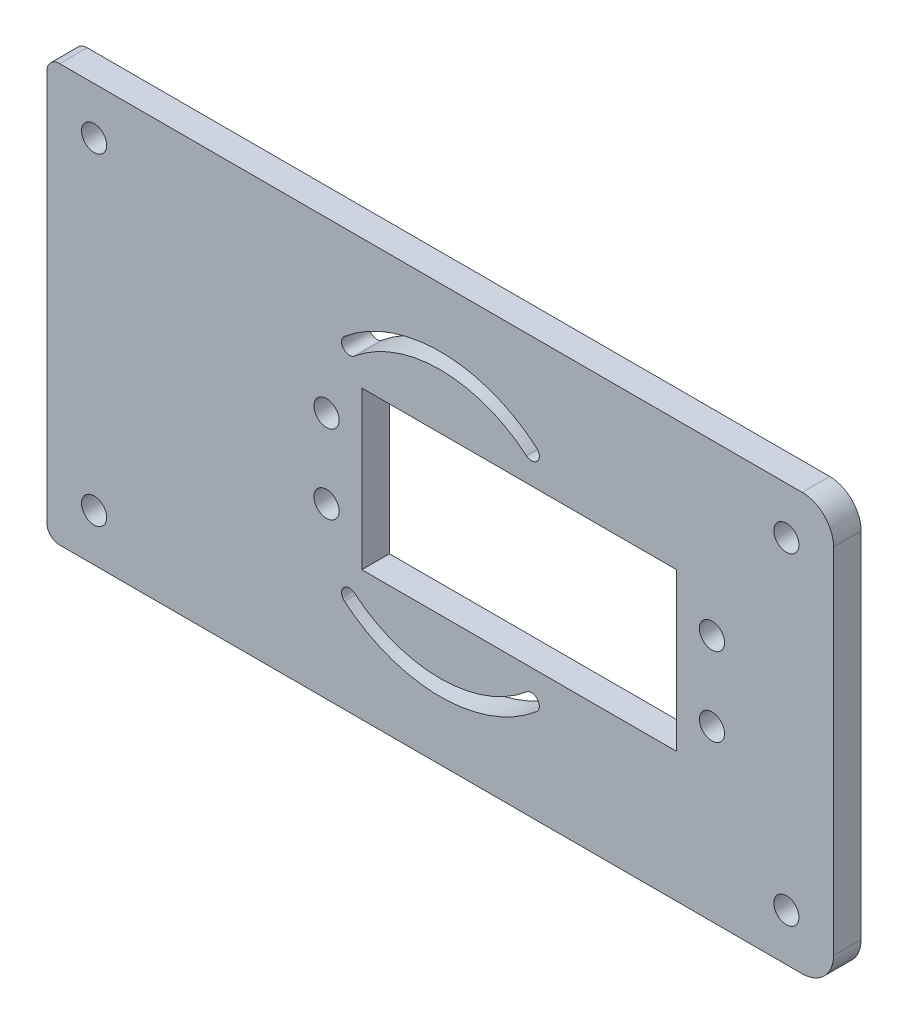
SolidWorks part; units mm, degrees
material "Balsa"
ref_plane "Front Plane" through (0, 0, 0) normal (0, 0, 1) x (1, 0, 0)
ref_plane "Top Plane" through (0, 0, 0) normal (0, 1, 0) x (1, 0, 0)
ref_plane "Right Plane" through (0, 0, 0) normal (1, 0, 0) x (0, 0, -1)
sketch "Sketch1" plane through (0, 0, 0) normal (0, 0, 1) x (1, 0, 0)
  line L5 (-0.0442, 0) -> (-0.0442, 26.5) construction
  line L6 (-48.429, -26.5) -> (48.3406, -26.5)
  line L34 (-50.0442, -24.8848) -> (-50.0442, 24.8848)
  line L37 (-48.429, 26.5) -> (48.3406, 26.5)
  line L41 (48.3406, 26.5) -> (45.9558, 26.5)
  line L42 (49.9558, 22.5) -> (49.9558, -22.5)
  line L47 (-0.0442, 0) -> (-0.0442, -26.5) construction
  line L48 (-0.0442, 0) -> (-50.0442, 0) construction
  line L49 (-0.0442, 0) -> (49.9558, 0) construction
  line L50 (-22.2361, -26.5) -> (22.2361, 26.5) construction
  line L51 (-22.2361, 26.5) -> (22.2361, -26.5) construction
  line L52 (45.9558, -26.5) -> (48.3406, -26.5)
  line L53 (10, -18.8302) -> (10, 13.0022) construction
  line L54 (-14.5, 9.5) -> (-14.5, -9.5) construction
  line L55 (34.5, -5) -> (34.5, 5) construction
  line L60 (34.5, 5) -> (-14.5, 5) construction
  line L61 (-10, 9.5) -> (-16.5, 9.5) construction
  line L62 (-10, -9.5) -> (-16.5, -9.5) construction
  line L63 (-10, 10) -> (30, 10)
  line L64 (-10, 10) -> (-10, -10)
  line L65 (-10, -10) -> (30, -10)
  line L66 (30, 10) -> (30, -10)
  line L67 (-14.5, 5) -> (-14.5, -5) construction
  line L68 (-14.5, -5) -> (34.5, -5) construction
  circle A7 centre (43.9558, -20.5) radius 1.6
  circle A8 centre (43.9558, 20.5) radius 1.6
  circle A9 centre (-44.0442, 20.5) radius 1.6
  circle A10 centre (-44.0442, -20.5) radius 1.6
  arc A15 (-48.429, -26.5) -> (-50.0442, -24.8848) centre (-48.429, -24.8848) cw
  arc A16 (-48.429, 26.5) -> (-50.0442, 24.8848) centre (-48.429, 24.8848) ccw
  arc A17 (-11.5884, -13.8105) -> (11.5519, -13.767) centre (-0.0442, 0) ccw construction
  arc A18 (-12.2298, -14.5778) -> (12.1961, -14.5318) centre (-0.0442, 0) ccw
  arc A19 (-10.9471, -13.0433) -> (10.9077, -13.0022) centre (-0.0442, 0) ccw
  arc A20 (-10.9471, -13.0433) -> (-12.2298, -14.5778) centre (-11.5884, -13.8105) ccw
  arc A21 (12.1961, -14.5318) -> (10.9077, -13.0022) centre (11.5519, -13.767) ccw
  arc A22 (-11.5884, 13.8105) -> (11.5519, 13.767) centre (-0.0442, 0) cw construction
  arc A23 (-12.2298, 14.5778) -> (12.1961, 14.5318) centre (-0.0442, 0) cw
  arc A24 (-10.9471, 13.0433) -> (10.9077, 13.0022) centre (-0.0442, 0) cw
  arc A25 (-10.9471, 13.0433) -> (-12.2298, 14.5778) centre (-11.5884, 13.8105) cw
  arc A26 (12.1961, 14.5318) -> (10.9077, 13.0022) centre (11.5519, 13.767) cw
  arc A28 (45.9558, 26.5) -> (49.9558, 22.5) centre (45.9558, 22.5) cw
  arc A29 (49.9558, -22.5) -> (45.9558, -26.5) centre (45.9558, -22.5) cw
  circle A37 centre (-14.5, 5) radius 1.6
  circle A38 centre (0, 0) radius 4.8808
  circle A39 centre (-14.5, -5) radius 1.6
  circle A40 centre (34.5, -5) radius 1.6
  circle A41 centre (34.5, 5) radius 1.6
  point P0 (0, 0)
  point P4 (-0.0103, -18)
  point P47 (-0.0103, 18)
  dimension "D6" = 6
  dimension "D11" = 49
  dimension "D1" = 3.2
  dimension "D14" = 40
  dimension "D18" = 10
  dimension "D24" = 18
  dimension "D10" = 4
  dimension "D13" = 20
  dimension "D17" = 10
  dimension "D16" = 3.2
  dimension "D12" = 5
  dimension "D2" = 6
  dimension "D3" = 6
  dimension "D4" = 6
  dimension "D5" = 6
  dimension "D7" = 6
  dimension "D8" = 6
  dimension "D9" = 6
  dimension "D15" = 100
  dimension "D19" = 50
  dimension "D21" = 50
  dimension "D23" = 53
  dimension "D25" = 2
extrude "Boss-Extrude1" add sketch "Sketch1" along normal blind 3.5
